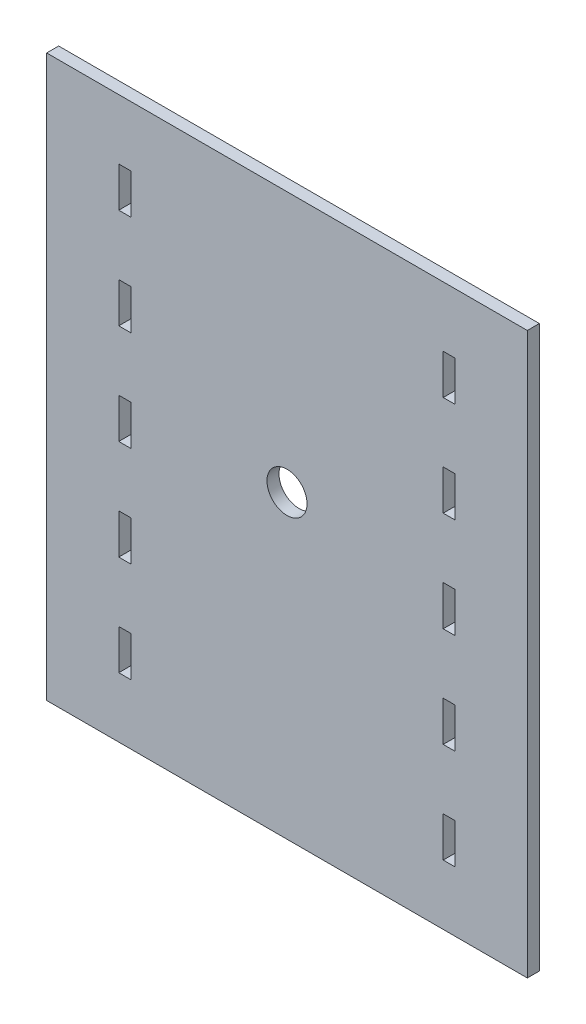
SolidWorks part; units mm, degrees
ref_plane "Plan de face" through (0, 0, 0) normal (0, 0, 1) x (1, 0, 0)
ref_plane "Plan de dessus" through (0, 0, 0) normal (0, 1, 0) x (1, 0, 0)
ref_plane "Plan de droite" through (0, 0, 0) normal (1, 0, 0) x (0, 0, -1)
sketch "Esquisse1" plane through (0, 0, 0) normal (0, 0, 1) x (1, 0, 0)
  line L1 (-39.992, 112.0219) -> (80.008, 112.0219)
  line L2 (-39.992, 112.0219) -> (-39.992, -27.9781)
  line L3 (-39.992, -27.9781) -> (80.008, -27.9781)
  line L4 (80.008, 112.0219) -> (80.008, -27.9781)
  dimension "D1" = 120
  dimension "D2" = 140
extrude "Boss.-Extru.1" add sketch "Esquisse1" along normal blind 3
sketch "Esquisse3" plane through (0, 0, 3) normal (0, 0, 1) x (1, 0, 0)
  line L0 (-21.992, 72.0219) -> (-18.992, 72.0219)
  line L1 (-21.992, 97.0219) -> (-18.992, 97.0219)
  line L2 (-21.992, 97.0219) -> (-21.992, 87.0219)
  line L3 (-21.992, 87.0219) -> (-18.992, 87.0219)
  line L4 (-18.992, 97.0219) -> (-18.992, 87.0219)
  line L5 (-21.992, 72.0219) -> (-21.992, 62.0219)
  line L6 (-21.992, 62.0219) -> (-18.992, 62.0219)
  line L7 (-18.992, 72.0219) -> (-18.992, 62.0219)
  line L8 (-21.992, -2.9781) -> (-18.992, -2.9781)
  line L9 (-21.992, -2.9781) -> (-21.992, -12.9781)
  line L10 (-21.992, -12.9781) -> (-18.992, -12.9781)
  line L11 (-18.992, -2.9781) -> (-18.992, -12.9781)
  line L12 (-39.992, 112.0219) -> (-39.992, -27.9781) construction
  line L13 (80.008, 112.0219) -> (-39.992, 112.0219) construction
  line L14 (-39.992, -27.9781) -> (80.008, -27.9781) construction
  line L15 (20.008, -27.9781) -> (20.008, 115.5243) construction
  line L28 (-21.992, 47.0219) -> (-18.992, 47.0219)
  line L29 (-21.992, 47.0219) -> (-21.992, 37.0219)
  line L30 (-21.992, 37.0219) -> (-18.992, 37.0219)
  line L31 (-18.992, 47.0219) -> (-18.992, 37.0219)
  line L32 (-21.992, 22.0219) -> (-18.992, 22.0219)
  line L33 (-21.992, 22.0219) -> (-21.992, 12.0219)
  line L34 (-21.992, 12.0219) -> (-18.992, 12.0219)
  line L35 (-18.992, 22.0219) -> (-18.992, 12.0219)
  line L36 (62.008, -2.9781) -> (62.008, -12.9781)
  line L37 (62.008, -12.9781) -> (59.008, -12.9781)
  line L38 (59.008, -2.9781) -> (59.008, -12.9781)
  line L39 (62.008, -2.9781) -> (59.008, -2.9781)
  line L40 (62.008, 22.0219) -> (62.008, 12.0219)
  line L41 (62.008, 12.0219) -> (59.008, 12.0219)
  line L42 (59.008, 22.0219) -> (59.008, 12.0219)
  line L43 (62.008, 22.0219) -> (59.008, 22.0219)
  line L44 (62.008, 47.0219) -> (62.008, 37.0219)
  line L45 (62.008, 37.0219) -> (59.008, 37.0219)
  line L46 (59.008, 47.0219) -> (59.008, 37.0219)
  line L47 (62.008, 47.0219) -> (59.008, 47.0219)
  line L48 (62.008, 72.0219) -> (62.008, 62.0219)
  line L49 (62.008, 62.0219) -> (59.008, 62.0219)
  line L50 (59.008, 72.0219) -> (59.008, 62.0219)
  line L51 (62.008, 72.0219) -> (59.008, 72.0219)
  line L52 (62.008, 87.0219) -> (59.008, 87.0219)
  line L53 (59.008, 97.0219) -> (59.008, 87.0219)
  line L54 (62.008, 97.0219) -> (59.008, 97.0219)
  line L55 (62.008, 97.0219) -> (62.008, 87.0219)
  circle A2 centre (20.008, 47.0219) radius 5
  point P40 (-20.492, 62.0219)
  point P41 (-21.992, 42.0219)
  dimension "D23" = 10
  dimension "D1" = 10
  dimension "D2" = 3
  dimension "D3" = 10
  dimension "D4" = 3
  dimension "D5" = 10
  dimension "D6" = 3
  dimension "D7" = 18
  dimension "D8" = 18
  dimension "D9" = 18
  dimension "D10" = 15
  dimension "D11" = 15
  dimension "D12" = 15
  dimension "D13" = 15
  dimension "D14" = 18
  dimension "D15" = 3
  dimension "D16" = 3
  dimension "D17" = 18
  dimension "D18" = 15
  dimension "D19" = 10
  dimension "D20" = 10
  dimension "D21" = 3
  dimension "D22" = 15
extrude "Enlèv. mat.-Extru.1" cut sketch "Esquisse3" against normal through all
